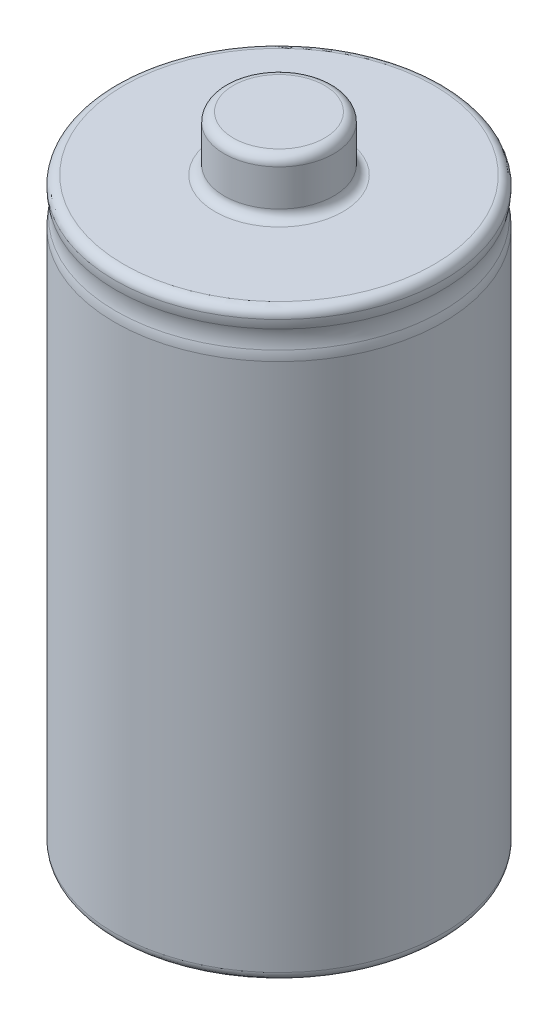
SolidWorks part; units mm, degrees
ref_plane "Front Plane" through (0, 0, 0) normal (0, 0, 1) x (1, 0, 0)
ref_plane "Top Plane" through (0, 0, 0) normal (0, 1, 0) x (1, 0, 0)
ref_plane "Right Plane" through (0, 0, 0) normal (1, 0, 0) x (0, 0, -1)
sketch "Sketch1" plane through (0, 0, 0) normal (0, 0, 1) x (1, 0, 0)
  line L0 (0, -17.5) -> (0, 17.5)
  line L1 (0, 17.5) -> (3, 17.5)
  line L2 (3, 17.5) -> (3, 14.5)
  line L3 (3, 14.5) -> (9, 14.5)
  line L4 (9, 14.5) -> (9, -17.5)
  line L5 (9, -17.5) -> (0, -17.5)
  dimension "D1" = 35
  dimension "D2" = 9
  dimension "D3" = 3
  dimension "D4" = 3
revolve "Revolve1" add sketch "Sketch1" angle 360 about L0
fillet "Fillet1" radius 0.5 4 edges at (0, 17.5, -3) (0, 14.5, -9) (0, 14.5, -3) (0, -17.5, -9)
sketch "Sketch2" plane through (0, 0, 0) normal (0, 0, 1) x (1, 0, 0)
  line L0 (0, 17.5) -> (0, -17.5)
  line L1 (2.5, 17.5) -> (-2.5, 17.5) construction
  line L2 (-9, -17.5) -> (9, -17.5) construction
  line L3 (9, -17) -> (9, 14) construction
  line L4 (9, 12) -> (9, 14)
  arc A0 (9, 14) -> (8.5, 14.5) centre (8.5, 14) ccw construction
  arc A1 (9, 14) -> (8.5, 14.5) centre (8.5, 14) ccw construction
  arc A2 (9, 14) -> (8.9365, 13.5) centre (7, 14) cw
  arc A3 (8.9365, 13.5) -> (8.9365, 12.5) centre (10.873, 13) ccw
  arc A4 (8.9365, 12.5) -> (9, 12) centre (7, 12) cw
  point P16 (0, 0)
  point P17 (7, 11.3845)
  dimension "D1" = 2
  dimension "D2" = 2
revolve "Cut-Revolve1" cut sketch "Sketch2" angle 360 about L0
